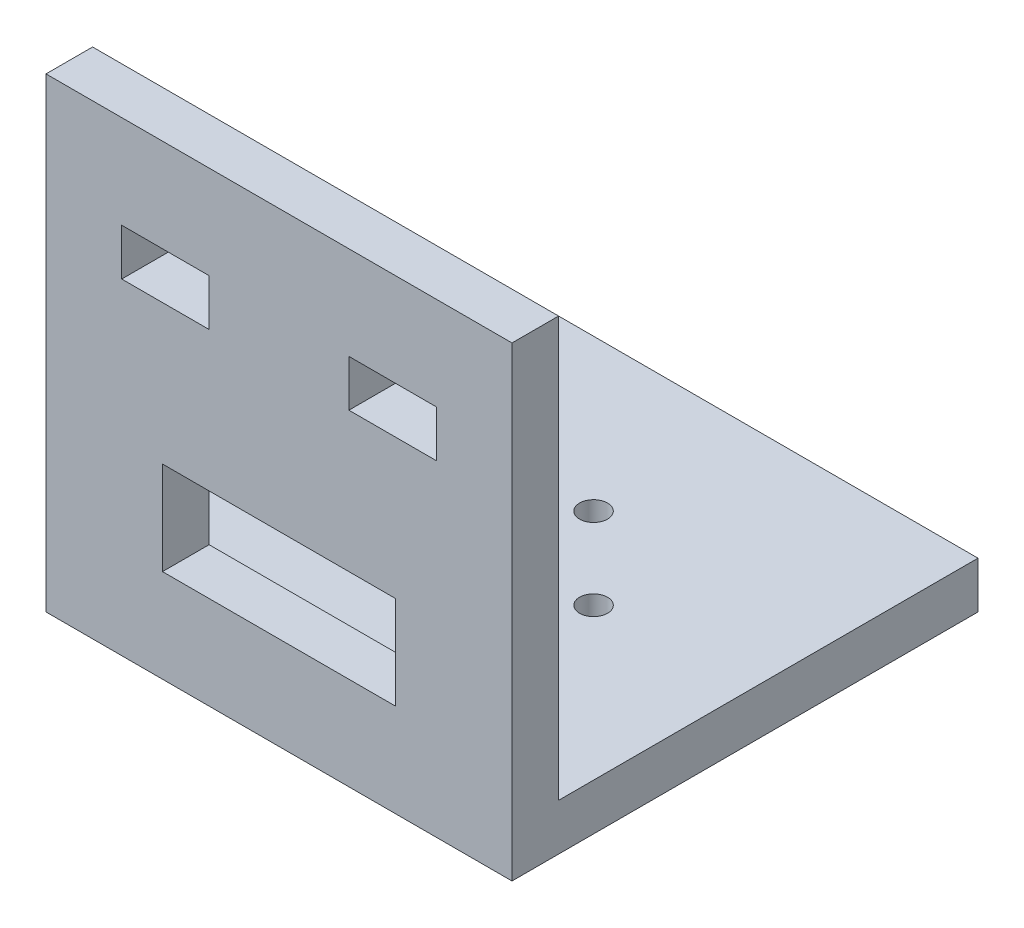
SolidWorks part; units mm, degrees
material "ABS"
ref_plane "Front Plane" through (0, 0, 0) normal (0, 0, 1) x (1, 0, 0)
ref_plane "Top Plane" through (0, 0, 0) normal (0, 1, 0) x (1, 0, 0)
ref_plane "Right Plane" through (0, 0, 0) normal (1, 0, 0) x (0, 0, -1)
sketch "Sketch1" plane through (0, 0, 0) normal (0, 1, 0) x (1, 0, 0)
  line L1 (-20, 20) -> (20, 20)
  line L2 (-20, 20) -> (-20, -20)
  line L3 (-20, -20) -> (20, -20)
  line L4 (20, 20) -> (20, -20)
  line L5 (-20, 20) -> (20, -20) construction
  line L6 (-20, -20) -> (20, 20) construction
  circle A0 centre (0, 0) radius 2
  circle A1 centre (7, 0) radius 1.2
  circle A2 centre (0, -7) radius 1.2
  circle A3 centre (-7, 0) radius 1.2
  circle A4 centre (0, 7) radius 1.2
  point P0 (0, 0)
  point P19 (0, 0)
  dimension "D3" = 4
  dimension "D4" = 2.4
  dimension "D1" = 40
  dimension "D2" = 40
  dimension "D5" = 7
  dimension "D6" = 4
extrude "Boss-Extrude1" add sketch "Sketch1" along normal blind 4
sketch "Sketch2" plane through (0, 0, 20) normal (0, 0, 1) x (1, 0, 0)
  line L1 (-20, 0) -> (20, 0)
  line L2 (-20, 0) -> (-20, 40)
  line L3 (-20, 40) -> (20, 40)
  line L4 (20, 0) -> (20, 40)
  dimension "D1" = 40
  dimension "D2" = 40
extrude "Boss-Extrude2" add sketch "Sketch2" against normal blind 4
sketch "Sketch3" plane through (0, 0, 20) normal (0, 0, 1) x (1, 0, 0)
  line L1 (-13.5, 32) -> (-6, 32)
  line L2 (-13.5, 32) -> (-13.5, 28)
  line L3 (-13.5, 28) -> (-6, 28)
  line L4 (-6, 32) -> (-6, 28)
  line L5 (6, 32) -> (13.5, 32)
  line L6 (6, 32) -> (6, 28)
  line L7 (6, 28) -> (13.5, 28)
  line L8 (13.5, 32) -> (13.5, 28)
  line L9 (-10, 16) -> (10, 16)
  line L10 (-10, 16) -> (-10, 8)
  line L11 (-10, 8) -> (10, 8)
  line L12 (10, 16) -> (10, 8)
  point P12 (0, 16)
  dimension "D1" = 20
  dimension "D2" = 8
  dimension "D3" = 8
  dimension "D4" = 4
  dimension "D5" = 4
  dimension "D6" = 4
  dimension "D7" = 4
  dimension "D8" = 7.5
  dimension "D9" = 7.5
  dimension "D10" = 12
extrude "Cut-Extrude1" cut sketch "Sketch3" against normal blind 4
